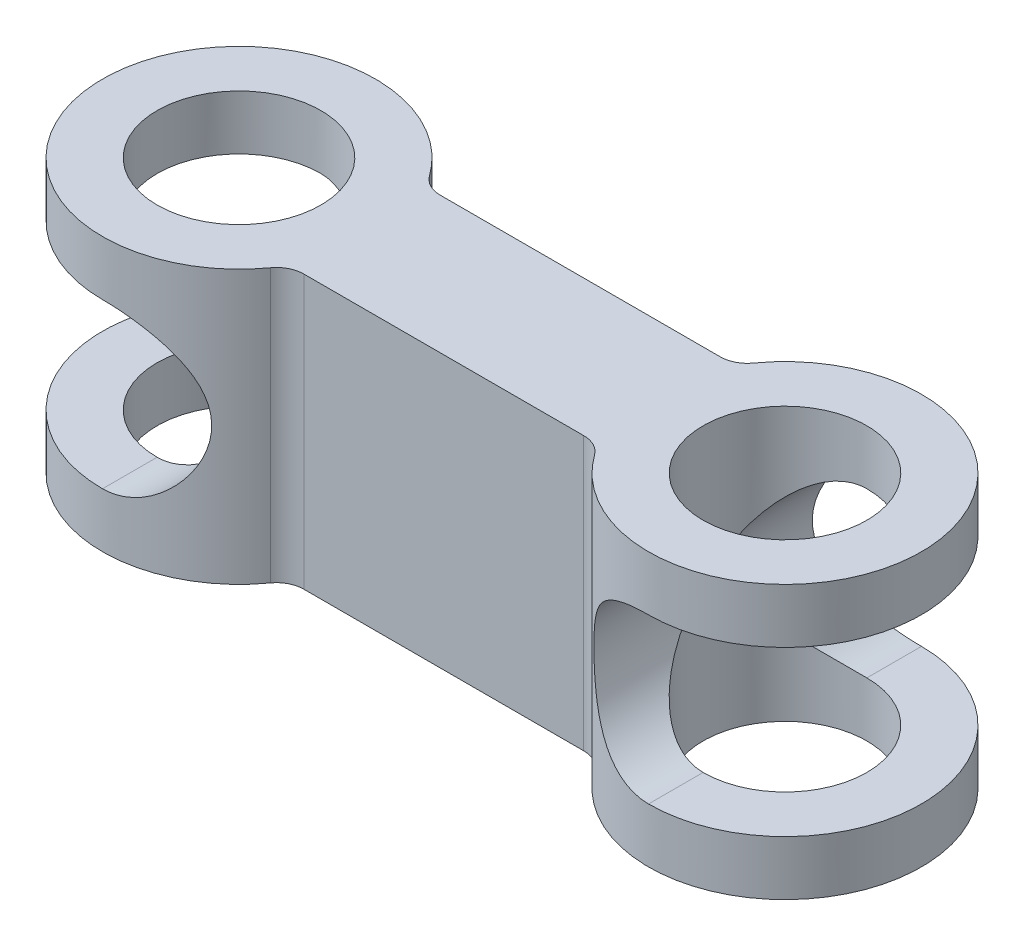
SolidWorks part; units mm, degrees
ref_plane "Front Plane" through (0, 0, 0) normal (0, 0, 1) x (1, 0, 0)
ref_plane "Top Plane" through (0, 0, 0) normal (0, 1, 0) x (1, 0, 0)
ref_plane "Right Plane" through (0, 0, 0) normal (1, 0, 0) x (0, 0, -1)
sketch "Sketch1" plane through (0, 0, 0) normal (0, 1, 0) x (1, 0, 0)
  line L1 (0, 2.5) -> (10, 2.5)
  line L2 (0, 2.5) -> (0, -2.5)
  line L3 (0, -2.5) -> (10, -2.5)
  line L4 (10, 2.5) -> (10, -2.5)
  dimension "D1" = 5
  dimension "D2" = 10
extrude "Boss-Extrude1" add sketch "Sketch1" along normal blind 10
sketch "Sketch2" plane through (0, 0, 0) normal (0, 1, 0) x (1, 0, 0)
  circle A0 centre (0, 0) radius 5
  dimension "D1" = 10
sketch "Sketch3" plane through (0, 0, 0) normal (0, 1, 0) x (1, 0, 0)
  circle A0 centre (0, 0) radius 3
  dimension "D1" = 6
extrude "Boss-Extrude2" add sketch "Sketch2" along normal up to surface (10 mm away) up to face at (5, 10, 0)
extrude "Cut-Extrude1" cut sketch "Sketch3" along normal up to next
sketch "Sketch4" plane through (0, 0, 0) normal (0, 0, 1) x (1, 0, 0)
  line L0 (0, 0) -> (0, 10) construction
  line L1 (3, 10) -> (-3, 10) construction
  line L2 (0, 8) -> (-5, 8)
  line L3 (-5, 10) -> (-5, 0) construction
  line L4 (0, 2) -> (-5, 2)
  line L5 (-5, 8) -> (-5, 2)
  arc A0 (0, 2) -> (0, 8) centre (0, 5) ccw
  dimension "D1" = 6
extrude "Cut-Extrude2" cut sketch "Sketch4" against normal through all both and the other way through all
fillet "Fillet1" radius 1 2 edges at (4.3301, 5, -2.5) (4.3301, 5, 2.5)
mirror "Mirror1" about plane through (10, 10, -2.5) normal (-1, 0, 0) of "Boss-Extrude1", "Cut-Extrude1", "Boss-Extrude2", "Cut-Extrude2", "Fillet1"
